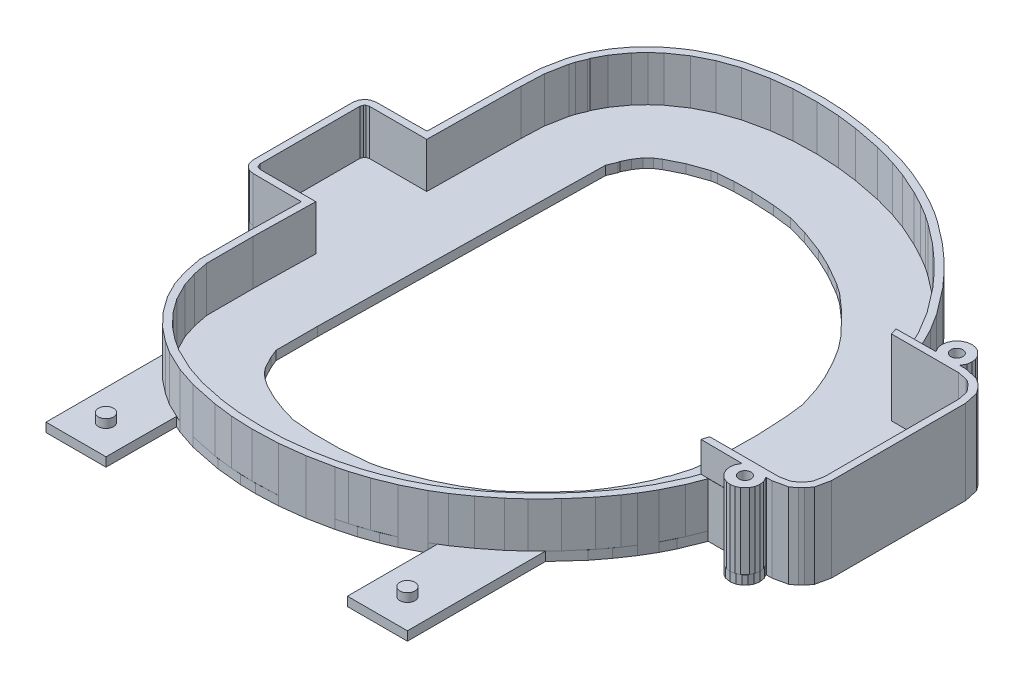
SolidWorks part; units mm, degrees
ref_plane "Front Plane" through (0, 0, 0) normal (0, 0, 1) x (1, 0, 0)
ref_plane "Top Plane" through (0, 0, 0) normal (0, 1, 0) x (1, 0, 0)
ref_plane "Right Plane" through (0, 0, 0) normal (1, 0, 0) x (0, 0, -1)
sketch "Sketch1" plane through (0, 0, 0) normal (0, 1, 0) x (1, 0, 0)
  line L0 (-54.2, 93.7) -> (-57.3, 91.7)
  line L1 (-57.3, 91.7) -> (-60.6, 89.2)
  line L2 (-60.6, 89.2) -> (-65.2, 84.7)
  line L3 (-65.2, 84.7) -> (-68.2, 80.8)
  line L4 (-68.2, 80.8) -> (-70, 77.9)
  line L5 (-70, 77.9) -> (-71.3, 75.3)
  line L6 (-71.3, 75.3) -> (-72.7, 71.6)
  line L7 (-72.7, 71.6) -> (-73.2, 69.9)
  line L8 (-73.2, 69.9) -> (-74.6, 62.9)
  line L9 (-74.6, 62.9) -> (-74.8, 61)
  line L10 (-74.8, 61) -> (-75.4, 26.1)
  line L11 (-75.4, 26.1) -> (-92.1, 26)
  line L12 (-92.1, 26) -> (-93.9, 25.6)
  line L13 (-93.9, 25.6) -> (-94.6, 25.1)
  line L14 (-94.6, 25.1) -> (-95.6, 23.9)
  line L15 (-95.6, 23.9) -> (-96, 22.1)
  line L16 (-96, 22.1) -> (-96, -11)
  line L17 (-96, -11) -> (-95.6, -12.8)
  line L18 (-95.6, -12.8) -> (-95.1, -13.5)
  line L19 (-95.1, -13.5) -> (-93.9, -14.5)
  line L20 (-93.9, -14.5) -> (-92.1, -14.9)
  line L21 (-92.1, -14.9) -> (-76, -15)
  line L22 (-76, -15) -> (-76.3, -33.1)
  line L23 (-76.3, -33.1) -> (-76.3, -48.4)
  line L24 (-76.3, -48.4) -> (-75.1, -54.4)
  line L25 (-75.1, -54.4) -> (-74, -58.1)
  line L26 (-74, -58.1) -> (-71.6, -63.3)
  line L27 (-71.6, -63.3) -> (-70, -65.8)
  line L28 (-70, -65.8) -> (-70, -105.7)
  line L29 (-70, -105.7) -> (-50.1, -105.7)
  line L30 (-50.1, -105.7) -> (-50, -82.4)
  line L31 (-50, -82.4) -> (-48, -83.3)
  line L32 (-48, -83.3) -> (-41.4, -85.5)
  line L33 (-41.4, -85.5) -> (-31.1, -87.6)
  line L34 (-31.1, -87.6) -> (-22.8, -88.4)
  line L35 (-22.8, -88.4) -> (-17.7, -88.5)
  line L36 (-17.7, -88.5) -> (-10.4, -88.2)
  line L37 (-10.4, -88.2) -> (-2.2, -87.2)
  line L38 (-2.2, -87.2) -> (5.8, -85.6)
  line L39 (5.8, -85.6) -> (11.6, -84)
  line L40 (11.6, -84) -> (17.1, -82.1)
  line L41 (17.1, -82.1) -> (21.4, -80.3)
  line L42 (21.4, -80.3) -> (28, -77)
  line L43 (28, -77) -> (29.8, -75.8)
  line L44 (29.8, -75.8) -> (30, -75.9)
  line L45 (30, -75.9) -> (30, -105.7)
  line L46 (30, -105.7) -> (49.9, -105.7)
  line L47 (49.9, -105.7) -> (49.9, -59.9)
  line L48 (49.9, -59.9) -> (56.6, -52.5)
  line L49 (56.6, -52.5) -> (60.1, -47.9)
  line L50 (60.1, -47.9) -> (63.5, -42.9)
  line L51 (63.5, -42.9) -> (66.1, -38.5)
  line L52 (66.1, -38.5) -> (68.1, -34.5)
  line L53 (68.1, -34.5) -> (71.1, -27.1)
  line L54 (71.1, -27.1) -> (82.2, -27.1)
  line L55 (82.2, -27.1) -> (82.3, -27.2)
  line L56 (82.3, -27.2) -> (81.5, -28.7)
  line L57 (81.5, -28.7) -> (81.3, -30.1)
  line L58 (81.3, -30.1) -> (81.5, -31.5)
  line L59 (81.5, -31.5) -> (82.1, -32.8)
  line L60 (82.1, -32.8) -> (83.3, -34.1)
  line L61 (83.3, -34.1) -> (84.6, -34.8)
  line L62 (84.6, -34.8) -> (86.3, -35.1)
  line L63 (86.3, -35.1) -> (88, -34.8)
  line L64 (88, -34.8) -> (89.3, -34.1)
  line L65 (89.3, -34.1) -> (90.3, -33.1)
  line L66 (90.3, -33.1) -> (91, -31.8)
  line L67 (91, -31.8) -> (91.3, -30.1)
  line L68 (91.3, -30.1) -> (91, -28.4)
  line L69 (91, -28.4) -> (90.3, -27.2)
  line L70 (90.3, -27.2) -> (90.4, -27.1)
  line L71 (90.4, -27.1) -> (92.2, -27.1)
  line L72 (92.2, -27.1) -> (96.8, -26.1)
  line L73 (96.8, -26.1) -> (98.7, -24.7)
  line L74 (98.7, -24.7) -> (99.7, -23.7)
  line L75 (99.7, -23.7) -> (101.1, -21.8)
  line L76 (101.1, -21.8) -> (102.1, -17.2)
  line L77 (102.1, -17.2) -> (102.1, 27.3)
  line L78 (102.1, 27.3) -> (101.1, 31.9)
  line L79 (101.1, 31.9) -> (99.7, 33.8)
  line L80 (99.7, 33.8) -> (98.7, 34.8)
  line L81 (98.7, 34.8) -> (96.8, 36.2)
  line L82 (96.8, 36.2) -> (92.2, 37.2)
  line L83 (92.2, 37.2) -> (90.4, 37.2)
  line L84 (90.4, 37.2) -> (90.3, 37.3)
  line L85 (90.3, 37.3) -> (91, 38.5)
  line L86 (91, 38.5) -> (91.3, 40.2)
  line L87 (91.3, 40.2) -> (91, 41.9)
  line L88 (91, 41.9) -> (90.3, 43.2)
  line L89 (90.3, 43.2) -> (89.3, 44.2)
  line L90 (89.3, 44.2) -> (88, 44.9)
  line L91 (88, 44.9) -> (86.3, 45.2)
  line L92 (86.3, 45.2) -> (84.6, 44.9)
  line L93 (84.6, 44.9) -> (83.3, 44.2)
  line L94 (83.3, 44.2) -> (82.1, 42.9)
  line L95 (82.1, 42.9) -> (81.5, 41.6)
  line L96 (81.5, 41.6) -> (81.3, 40.2)
  line L97 (81.3, 40.2) -> (81.5, 38.8)
  line L98 (81.5, 38.8) -> (82.3, 37.3)
  line L99 (82.3, 37.3) -> (82.2, 37.2)
  line L100 (82.2, 37.2) -> (71.7, 37.2)
  line L101 (71.7, 37.2) -> (68.9, 45.1)
  line L102 (68.9, 45.1) -> (66.3, 50.5)
  line L103 (66.3, 50.5) -> (64.5, 53.7)
  line L104 (64.5, 53.7) -> (61.7, 58.1)
  line L105 (61.7, 58.1) -> (58.4, 62.6)
  line L106 (58.4, 62.6) -> (55.2, 66.6)
  line L107 (55.2, 66.6) -> (51.5, 70.7)
  line L108 (51.5, 70.7) -> (47.1, 75.1)
  line L109 (47.1, 75.1) -> (43.7, 78.2)
  line L110 (43.7, 78.2) -> (39.9, 81.3)
  line L111 (39.9, 81.3) -> (33.5, 86)
  line L112 (33.5, 86) -> (25.7, 90.6)
  line L113 (25.7, 90.6) -> (17.4, 94.4)
  line L114 (17.4, 94.4) -> (11.8, 96.4)
  line L115 (11.8, 96.4) -> (7, 97.8)
  line L116 (7, 97.8) -> (-4, 100.1)
  line L117 (-4, 100.1) -> (-12.8, 101.2)
  line L118 (-12.8, 101.2) -> (-22, 101.5)
  line L119 (-22, 101.5) -> (-30.2, 101)
  line L120 (-30.2, 101) -> (-33.6, 100.5)
  line L121 (-33.6, 100.5) -> (-40.9, 99)
  line L122 (-40.9, 99) -> (-47.8, 96.8)
  line L123 (-47.8, 96.8) -> (-54.2, 93.7)
  line L124 (-30.2, 77.2) -> (-25.1, 77.6)
  line L125 (-25.1, 77.6) -> (-19.1, 77.7)
  line L126 (-19.1, 77.7) -> (-11.6, 77.3)
  line L127 (-11.6, 77.3) -> (-5.2, 76.5)
  line L128 (-5.2, 76.5) -> (1.2, 74.7)
  line L129 (1.2, 74.7) -> (8.7, 71.9)
  line L130 (8.7, 71.9) -> (14.8, 69)
  line L131 (14.8, 69) -> (21.4, 65.2)
  line L132 (21.4, 65.2) -> (24.7, 62.9)
  line L133 (24.7, 62.9) -> (30.6, 57.7)
  line L134 (30.6, 57.7) -> (37.2, 50.8)
  line L135 (37.2, 50.8) -> (40.3, 46.9)
  line L136 (40.3, 46.9) -> (43.2, 42.3)
  line L137 (43.2, 42.3) -> (46.3, 36.4)
  line L138 (46.3, 36.4) -> (48.4, 31.4)
  line L139 (48.4, 31.4) -> (50.5, 24.7)
  line L140 (50.5, 24.7) -> (51.2, 18.7)
  line L141 (51.2, 18.7) -> (51.7, 8.7)
  line L142 (51.7, 8.7) -> (51.6, -1.8)
  line L143 (51.6, -1.8) -> (51.1, -8.8)
  line L144 (51.1, -8.8) -> (50.7, -11.9)
  line L145 (50.7, -11.9) -> (49, -17.6)
  line L146 (49, -17.6) -> (48.5, -18.5)
  line L147 (48.5, -18.5) -> (47.4, -21.6)
  line L148 (47.4, -21.6) -> (44.5, -27.6)
  line L149 (44.5, -27.6) -> (41.9, -32)
  line L150 (41.9, -32) -> (39.1, -36.1)
  line L151 (39.1, -36.1) -> (33.7, -42.2)
  line L152 (33.7, -42.2) -> (27.1, -48.5)
  line L153 (27.1, -48.5) -> (24.3, -50.8)
  line L154 (24.3, -50.8) -> (21.7, -52.6)
  line L155 (21.7, -52.6) -> (17.1, -55.4)
  line L156 (17.1, -55.4) -> (10.5, -58.7)
  line L157 (10.5, -58.7) -> (4, -61.3)
  line L158 (4, -61.3) -> (-1.3, -63)
  line L159 (-1.3, -63) -> (-4.2, -63.7)
  line L160 (-4.2, -63.7) -> (-13.8, -64.6)
  line L161 (-13.8, -64.6) -> (-22.8, -64.6)
  line L162 (-22.8, -64.6) -> (-29.7, -64)
  line L163 (-29.7, -64) -> (-33.7, -62.9)
  line L164 (-33.7, -62.9) -> (-39.2, -60.8)
  line L165 (-39.2, -60.8) -> (-43.6, -58.6)
  line L166 (-43.6, -58.6) -> (-46.3, -56.8)
  line L167 (-46.3, -56.8) -> (-48.1, -55.1)
  line L168 (-48.1, -55.1) -> (-49.3, -53.6)
  line L169 (-49.3, -53.6) -> (-51.3, -49.8)
  line L170 (-51.3, -49.8) -> (-52.5, -46.9)
  line L171 (-52.5, -46.9) -> (-52.5, -33.1)
  line L172 (-52.5, -33.1) -> (-51, 61)
  line L173 (-51, 61) -> (-49.8, 63.8)
  line L174 (-49.8, 63.8) -> (-49.7, 64.4)
  line L175 (-49.7, 64.4) -> (-48.4, 67)
  line L176 (-48.4, 67) -> (-46.9, 69.2)
  line L177 (-46.9, 69.2) -> (-45.1, 70.9)
  line L178 (-45.1, 70.9) -> (-43.3, 72.1)
  line L179 (-43.3, 72.1) -> (-38.1, 74.7)
  line L180 (-38.1, 74.7) -> (-31.9, 76.9)
  line L181 (-31.9, 76.9) -> (-30.2, 77.2)
extrude "Floor (ring + tongues)" add sketch "Sketch1" along normal blind 3
ref_plane "P1_Top_3" through (0, 3, 0) normal (0, 1, 0) x (1, 0, 0)
sketch "Sketch2" plane through (0, 3, 0) normal (0, 1, 0) x (1, 0, 0)
  line L0 (-26.8, 101.3) -> (-33.6, 100.5)
  line L1 (-33.6, 100.5) -> (-42.5, 98.6)
  line L2 (-42.5, 98.6) -> (-49, 96.3)
  line L3 (-49, 96.3) -> (-54.2, 93.7)
  line L4 (-54.2, 93.7) -> (-57.3, 91.7)
  line L5 (-57.3, 91.7) -> (-60.1, 89.6)
  line L6 (-60.1, 89.6) -> (-62.9, 87.1)
  line L7 (-62.9, 87.1) -> (-65.7, 84.1)
  line L8 (-65.7, 84.1) -> (-68.6, 80.2)
  line L9 (-68.6, 80.2) -> (-71.3, 75.3)
  line L10 (-71.3, 75.3) -> (-72.6, 71.9)
  line L11 (-72.6, 71.9) -> (-73.2, 69.9)
  line L12 (-73.2, 69.9) -> (-74.6, 62.9)
  line L13 (-74.6, 62.9) -> (-75, 54.6)
  line L14 (-75, 54.6) -> (-75.4, 26.1)
  line L15 (-75.4, 26.1) -> (-92.1, 26)
  line L16 (-92.1, 26) -> (-93.9, 25.6)
  line L17 (-93.9, 25.6) -> (-95.1, 24.6)
  line L18 (-95.1, 24.6) -> (-95.7, 23.6)
  line L19 (-95.7, 23.6) -> (-96, 22.1)
  line L20 (-96, 22.1) -> (-96, -11)
  line L21 (-96, -11) -> (-95.6, -12.8)
  line L22 (-95.6, -12.8) -> (-94.6, -14)
  line L23 (-94.6, -14) -> (-93.6, -14.6)
  line L24 (-93.6, -14.6) -> (-92.1, -14.9)
  line L25 (-92.1, -14.9) -> (-76, -15)
  line L26 (-76, -15) -> (-76.3, -33.1)
  line L27 (-76.3, -33.1) -> (-76.3, -48.4)
  line L28 (-76.3, -48.4) -> (-75.1, -54.4)
  line L29 (-75.1, -54.4) -> (-73.5, -59.4)
  line L30 (-73.5, -59.4) -> (-70.9, -64.5)
  line L31 (-70.9, -64.5) -> (-67, -69.9)
  line L32 (-67, -69.9) -> (-62.8, -74.2)
  line L33 (-62.8, -74.2) -> (-58.5, -77.6)
  line L34 (-58.5, -77.6) -> (-54.5, -80.2)
  line L35 (-54.5, -80.2) -> (-48, -83.3)
  line L36 (-48, -83.3) -> (-41.4, -85.5)
  line L37 (-41.4, -85.5) -> (-32.3, -87.4)
  line L38 (-32.3, -87.4) -> (-25.9, -88.2)
  line L39 (-25.9, -88.2) -> (-18.9, -88.5)
  line L40 (-18.9, -88.5) -> (-10.4, -88.2)
  line L41 (-10.4, -88.2) -> (-2.2, -87.2)
  line L42 (-2.2, -87.2) -> (5.8, -85.6)
  line L43 (5.8, -85.6) -> (9.3, -84.7)
  line L44 (9.3, -84.7) -> (14.9, -82.9)
  line L45 (14.9, -82.9) -> (21.4, -80.3)
  line L46 (21.4, -80.3) -> (28, -77)
  line L47 (28, -77) -> (32.3, -74.4)
  line L48 (32.3, -74.4) -> (37.3, -70.9)
  line L49 (37.3, -70.9) -> (42.9, -66.5)
  line L50 (42.9, -66.5) -> (47, -62.8)
  line L51 (47, -62.8) -> (52.5, -57.2)
  line L52 (52.5, -57.2) -> (57.7, -51.1)
  line L53 (57.7, -51.1) -> (61.3, -46.2)
  line L54 (61.3, -46.2) -> (63.5, -42.9)
  line L55 (63.5, -42.9) -> (66.1, -38.5)
  line L56 (66.1, -38.5) -> (69, -32.5)
  line L57 (69, -32.5) -> (71.1, -27.1)
  line L58 (71.1, -27.1) -> (92.2, -27.1)
  line L59 (92.2, -27.1) -> (96.8, -26.1)
  line L60 (96.8, -26.1) -> (98.7, -24.7)
  line L61 (98.7, -24.7) -> (99.7, -23.7)
  line L62 (99.7, -23.7) -> (101.1, -21.8)
  line L63 (101.1, -21.8) -> (102.1, -17.2)
  line L64 (102.1, -17.2) -> (102.1, 27.3)
  line L65 (102.1, 27.3) -> (101.1, 31.9)
  line L66 (101.1, 31.9) -> (99.7, 33.8)
  line L67 (99.7, 33.8) -> (98.7, 34.8)
  line L68 (98.7, 34.8) -> (96.8, 36.2)
  line L69 (96.8, 36.2) -> (92.2, 37.2)
  line L70 (92.2, 37.2) -> (71.7, 37.2)
  line L71 (71.7, 37.2) -> (68.9, 45.1)
  line L72 (68.9, 45.1) -> (65.2, 52.5)
  line L73 (65.2, 52.5) -> (61.7, 58.1)
  line L74 (61.7, 58.1) -> (55.2, 66.6)
  line L75 (55.2, 66.6) -> (51.5, 70.7)
  line L76 (51.5, 70.7) -> (47.1, 75.1)
  line L77 (47.1, 75.1) -> (42.4, 79.3)
  line L78 (42.4, 79.3) -> (35.5, 84.6)
  line L79 (35.5, 84.6) -> (32.3, 86.8)
  line L80 (32.3, 86.8) -> (28.6, 89)
  line L81 (28.6, 89) -> (24.3, 91.3)
  line L82 (24.3, 91.3) -> (17.4, 94.4)
  line L83 (17.4, 94.4) -> (11.8, 96.4)
  line L84 (11.8, 96.4) -> (5, 98.3)
  line L85 (5, 98.3) -> (-4, 100.1)
  line L86 (-4, 100.1) -> (-11.6, 101.1)
  line L87 (-11.6, 101.1) -> (-19.1, 101.5)
  line L88 (-19.1, 101.5) -> (-26.8, 101.3)
  line L89 (-26.8, 99) -> (-19.1, 99.2)
  line L90 (-19.1, 99.2) -> (-11.6, 98.8)
  line L91 (-11.6, 98.8) -> (-5.2, 98)
  line L92 (-5.2, 98) -> (4, 96.2)
  line L93 (4, 96.2) -> (10.8, 94.3)
  line L94 (10.8, 94.3) -> (16.1, 92.4)
  line L95 (16.1, 92.4) -> (23, 89.3)
  line L96 (23, 89.3) -> (27.7, 86.8)
  line L97 (27.7, 86.8) -> (31.4, 84.6)
  line L98 (31.4, 84.6) -> (34.3, 82.6)
  line L99 (34.3, 82.6) -> (40.8, 77.6)
  line L100 (40.8, 77.6) -> (45.5, 73.4)
  line L101 (45.5, 73.4) -> (49.8, 69.1)
  line L102 (49.8, 69.1) -> (53.5, 65)
  line L103 (53.5, 65) -> (59.7, 56.9)
  line L104 (59.7, 56.9) -> (64.1, 49.6)
  line L105 (64.1, 49.6) -> (67.6, 42.1)
  line L106 (67.6, 42.1) -> (69.2, 37.5)
  line L107 (69.2, 37.5) -> (69.9, 34.9)
  line L108 (69.9, 34.9) -> (92.2, 34.9)
  line L109 (92.2, 34.9) -> (95.2, 34.3)
  line L110 (95.2, 34.3) -> (95.9, 34)
  line L111 (95.9, 34) -> (97.1, 33.1)
  line L112 (97.1, 33.1) -> (98.9, 31)
  line L113 (98.9, 31) -> (99.2, 30.3)
  line L114 (99.2, 30.3) -> (99.8, 27.3)
  line L115 (99.8, 27.3) -> (99.8, -17.2)
  line L116 (99.8, -17.2) -> (99.1, -20.5)
  line L117 (99.1, -20.5) -> (98, -22.1)
  line L118 (98, -22.1) -> (97.1, -23)
  line L119 (97.1, -23) -> (95.5, -24.1)
  line L120 (95.5, -24.1) -> (92.2, -24.8)
  line L121 (92.2, -24.8) -> (69.3, -24.8)
  line L122 (69.3, -24.8) -> (67.6, -29.8)
  line L123 (67.6, -29.8) -> (63.9, -37.6)
  line L124 (63.9, -37.6) -> (61.3, -42)
  line L125 (61.3, -42) -> (58.1, -46.7)
  line L126 (58.1, -46.7) -> (53.4, -52.7)
  line L127 (53.4, -52.7) -> (49.4, -57.1)
  line L128 (49.4, -57.1) -> (44.1, -62.3)
  line L129 (44.1, -62.3) -> (38.1, -67.4)
  line L130 (38.1, -67.4) -> (31.7, -72)
  line L131 (31.7, -72) -> (27.1, -74.8)
  line L132 (27.1, -74.8) -> (21.4, -77.7)
  line L133 (21.4, -77.7) -> (15.8, -80.1)
  line L134 (15.8, -80.1) -> (10.6, -81.9)
  line L135 (10.6, -81.9) -> (4.8, -83.5)
  line L136 (4.8, -83.5) -> (-2.2, -84.9)
  line L137 (-2.2, -84.9) -> (-10.4, -85.9)
  line L138 (-10.4, -85.9) -> (-17.7, -86.2)
  line L139 (-17.7, -86.2) -> (-25.9, -85.9)
  line L140 (-25.9, -85.9) -> (-32.3, -85.1)
  line L141 (-32.3, -85.1) -> (-40.4, -83.4)
  line L142 (-40.4, -83.4) -> (-46.7, -81.3)
  line L143 (-46.7, -81.3) -> (-53.6, -78)
  line L144 (-53.6, -78) -> (-57.3, -75.6)
  line L145 (-57.3, -75.6) -> (-61.2, -72.5)
  line L146 (-61.2, -72.5) -> (-65.3, -68.3)
  line L147 (-65.3, -68.3) -> (-68.7, -63.6)
  line L148 (-68.7, -63.6) -> (-71.5, -58.1)
  line L149 (-71.5, -58.1) -> (-73, -53.4)
  line L150 (-73, -53.4) -> (-74, -48.4)
  line L151 (-74, -48.4) -> (-74, -33.1)
  line L152 (-74, -33.1) -> (-73.6, -12.6)
  line L153 (-73.6, -12.6) -> (-92.1, -12.6)
  line L154 (-92.1, -12.6) -> (-93, -12.3)
  line L155 (-93, -12.3) -> (-93.4, -11.9)
  line L156 (-93.4, -11.9) -> (-93.7, -11)
  line L157 (-93.7, -11) -> (-93.7, 22.1)
  line L158 (-93.7, 22.1) -> (-93.4, 23)
  line L159 (-93.4, 23) -> (-93, 23.4)
  line L160 (-93, 23.4) -> (-92.1, 23.7)
  line L161 (-92.1, 23.7) -> (-73.1, 23.7)
  line L162 (-73.1, 23.7) -> (-72.7, 54.6)
  line L163 (-72.7, 54.6) -> (-72.4, 62)
  line L164 (-72.4, 62) -> (-71.1, 68.9)
  line L165 (-71.1, 68.9) -> (-70.6, 70.6)
  line L166 (-70.6, 70.6) -> (-69.4, 73.4)
  line L167 (-69.4, 73.4) -> (-69.3, 74)
  line L168 (-69.3, 74) -> (-67.2, 78)
  line L169 (-67.2, 78) -> (-64, 82.5)
  line L170 (-64, 82.5) -> (-61.3, 85.4)
  line L171 (-61.3, 85.4) -> (-58.5, 87.9)
  line L172 (-58.5, 87.9) -> (-53.3, 91.5)
  line L173 (-53.3, 91.5) -> (-47.7, 94.3)
  line L174 (-47.7, 94.3) -> (-41.5, 96.5)
  line L175 (-41.5, 96.5) -> (-33.6, 98.2)
  line L176 (-33.6, 98.2) -> (-26.8, 99)
extrude "Rim" add sketch "Sketch2" along normal blind 15
ref_plane "P2_Top_3" through (0, 3, 0) normal (0, 1, 0) x (1, 0, 0)
sketch "Sketch3" plane through (0, 3, 0) normal (0, 1, 0) x (1, 0, 0)
  line L0 (86.3, 45.2) -> (84.9, 45)
  line L1 (84.9, 45) -> (83.6, 44.4)
  line L2 (83.6, 44.4) -> (82.1, 42.9)
  line L3 (82.1, 42.9) -> (81.5, 41.6)
  line L4 (81.5, 41.6) -> (81.3, 40.2)
  line L5 (81.3, 40.2) -> (81.5, 38.8)
  line L6 (81.5, 38.8) -> (82.3, 37.3)
  line L7 (82.3, 37.3) -> (82.2, 37.2)
  line L8 (82.2, 37.2) -> (69.2, 37.1)
  line L9 (69.2, 37.1) -> (69.9, 34.9)
  line L10 (69.9, 34.9) -> (92.2, 34.9)
  line L11 (92.2, 34.9) -> (95.2, 34.3)
  line L12 (95.2, 34.3) -> (95.9, 34)
  line L13 (95.9, 34) -> (97.1, 33.1)
  line L14 (97.1, 33.1) -> (98.9, 31)
  line L15 (98.9, 31) -> (99.2, 30.3)
  line L16 (99.2, 30.3) -> (99.8, 27.3)
  line L17 (99.8, 27.3) -> (99.8, -17.2)
  line L18 (99.8, -17.2) -> (99.2, -20.2)
  line L19 (99.2, -20.2) -> (98.9, -20.9)
  line L20 (98.9, -20.9) -> (98, -22.1)
  line L21 (98, -22.1) -> (97.1, -23)
  line L22 (97.1, -23) -> (95.9, -23.9)
  line L23 (95.9, -23.9) -> (95.2, -24.2)
  line L24 (95.2, -24.2) -> (92.2, -24.8)
  line L25 (92.2, -24.8) -> (69.3, -24.8)
  line L26 (69.3, -24.8) -> (68.6, -27)
  line L27 (68.6, -27) -> (82.2, -27.1)
  line L28 (82.2, -27.1) -> (82.3, -27.2)
  line L29 (82.3, -27.2) -> (81.5, -28.7)
  line L30 (81.5, -28.7) -> (81.3, -30.1)
  line L31 (81.3, -30.1) -> (81.5, -31.5)
  line L32 (81.5, -31.5) -> (82.1, -32.8)
  line L33 (82.1, -32.8) -> (83.6, -34.3)
  line L34 (83.6, -34.3) -> (84.9, -34.9)
  line L35 (84.9, -34.9) -> (86.3, -35.1)
  line L36 (86.3, -35.1) -> (87.7, -34.9)
  line L37 (87.7, -34.9) -> (89, -34.3)
  line L38 (89, -34.3) -> (90.5, -32.8)
  line L39 (90.5, -32.8) -> (91.1, -31.5)
  line L40 (91.1, -31.5) -> (91.3, -30.1)
  line L41 (91.3, -30.1) -> (91.1, -28.7)
  line L42 (91.1, -28.7) -> (90.3, -27.2)
  line L43 (90.3, -27.2) -> (90.4, -27.1)
  line L44 (90.4, -27.1) -> (92.2, -27.1)
  line L45 (92.2, -27.1) -> (96.8, -26.1)
  line L46 (96.8, -26.1) -> (98.7, -24.7)
  line L47 (98.7, -24.7) -> (99.7, -23.7)
  line L48 (99.7, -23.7) -> (101.1, -21.8)
  line L49 (101.1, -21.8) -> (102.1, -17.2)
  line L50 (102.1, -17.2) -> (102.1, 27.3)
  line L51 (102.1, 27.3) -> (101.1, 31.9)
  line L52 (101.1, 31.9) -> (99.7, 33.8)
  line L53 (99.7, 33.8) -> (98.7, 34.8)
  line L54 (98.7, 34.8) -> (96.8, 36.2)
  line L55 (96.8, 36.2) -> (92.2, 37.2)
  line L56 (92.2, 37.2) -> (90.4, 37.2)
  line L57 (90.4, 37.2) -> (90.3, 37.3)
  line L58 (90.3, 37.3) -> (91.1, 38.8)
  line L59 (91.1, 38.8) -> (91.3, 40.2)
  line L60 (91.3, 40.2) -> (91.1, 41.6)
  line L61 (91.1, 41.6) -> (90.5, 42.9)
  line L62 (90.5, 42.9) -> (89, 44.4)
  line L63 (89, 44.4) -> (87.7, 45)
  line L64 (87.7, 45) -> (86.3, 45.2)
extrude "Pedal hood walls" add sketch "Sketch3" along normal blind 25
ref_plane "P3_Top_28" through (0, 28, 0) normal (0, 1, 0) x (1, 0, 0)
sketch "Sketch4" plane through (0, 28, 0) normal (0, 1, 0) x (1, 0, 0)
  circle A0 centre (86.28, 40.2) radius 2
  circle A1 centre (86.28, -30.1) radius 2
extrude "Cover insert holes" cut sketch "Sketch4" against normal blind 7
ref_plane "P4_Top_3" through (0, 3, 0) normal (0, 1, 0) x (1, 0, 0)
sketch "Sketch5" plane through (0, 3, 0) normal (0, 1, 0) x (1, 0, 0)
  circle A0 centre (-60, -95.8) radius 2.5
  circle A1 centre (40, -95.8) radius 2.5
extrude "Box pegs" add sketch "Sketch5" along normal blind 2.8
